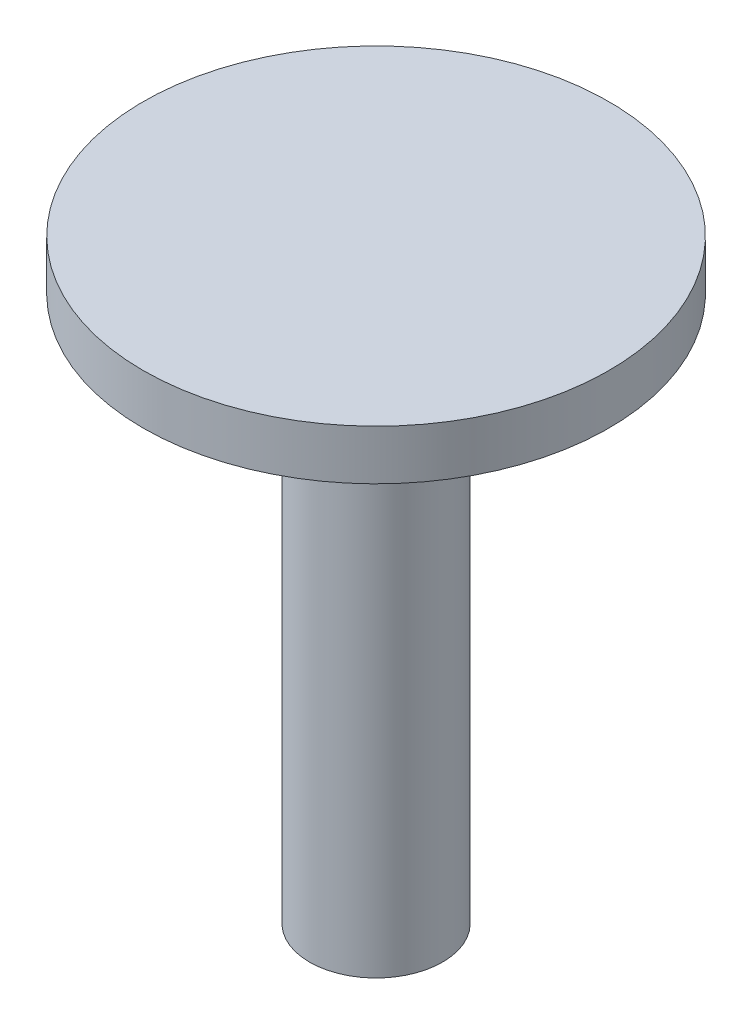
SolidWorks part; units mm, degrees
material "Acciaio al carbonio semplice"
ref_plane "Piano frontale" through (0, 0, 0) normal (0, 0, 1) x (1, 0, 0)
ref_plane "Piano superiore" through (0, 0, 0) normal (0, 1, 0) x (1, 0, 0)
ref_plane "Piano destro" through (0, 0, 0) normal (1, 0, 0) x (0, 0, -1)
sketch "Schizzo1" plane through (0, 0, 0) normal (0, 0, 1) x (1, 0, 0)
  line L0 (-4, 0) -> (-4, 32.8)
  line L1 (-4, 32.8) -> (-14, 32.8)
  line L2 (-14, 32.8) -> (-14, 35.8)
  line L3 (-14, 35.8) -> (0, 35.8)
  line L4 (0, 35.8) -> (0, 0)
  line L5 (0, 0) -> (-4, 0)
  line L6 (0, 0) -> (0, -5.4799) construction
  dimension "D1" = 8
  dimension "D2" = 35.8
  dimension "D3" = 3
  dimension "D4" = 28
revolve "Rivoluzione1" add sketch "Schizzo1" angle 360 about L6
